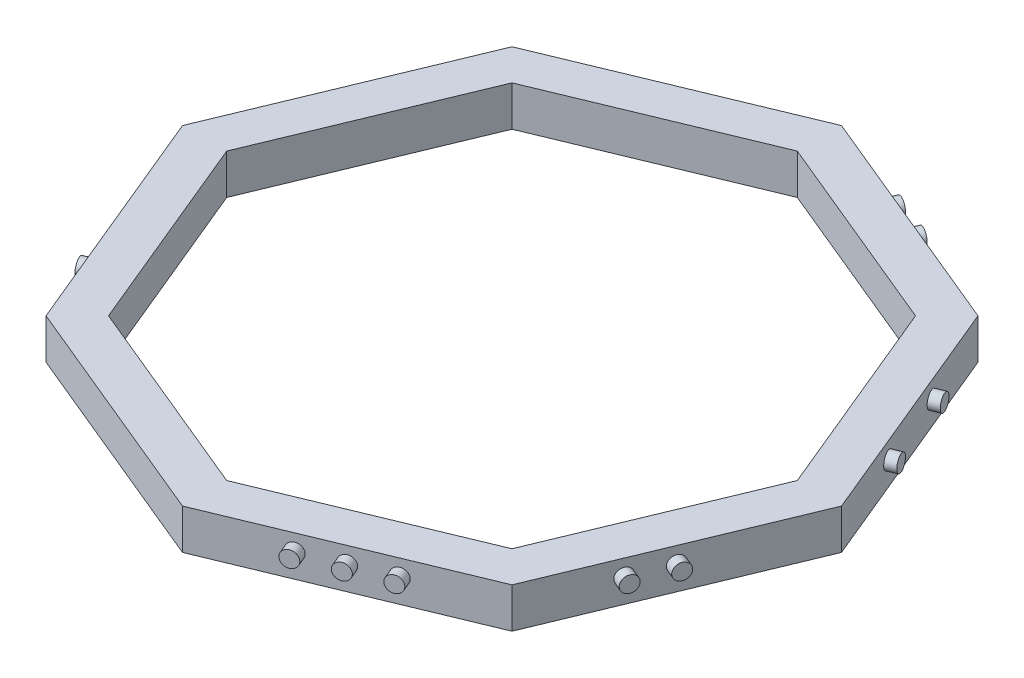
SolidWorks part; units mm, degrees
ref_plane "Front Plane" through (0, 0, 0) normal (0, 0, 1) x (1, 0, 0)
ref_plane "Top Plane" through (0, 0, 0) normal (0, 1, 0) x (1, 0, 0)
ref_plane "Right Plane" through (0, 0, 0) normal (1, 0, 0) x (0, 0, -1)
sketch "Sketch3" plane through (0, 0, 0) normal (0, 1, 0) x (1, 0, 0)
  line L1 (41, 0) -> (28.9914, 28.9914)
  line L2 (28.9914, 28.9914) -> (0, 41)
  line L3 (0, 41) -> (-28.9914, 28.9914)
  line L4 (-28.9914, 28.9914) -> (-41, 0)
  line L5 (-41, 0) -> (-28.9914, -28.9914)
  line L6 (-28.9914, -28.9914) -> (0, -41)
  line L7 (0, -41) -> (28.9914, -28.9914)
  line L8 (28.9914, -28.9914) -> (41, 0)
  circle A0 centre (0, 0) radius 37.8791 construction
  dimension "D1" = 41
extrude "Boss-Extrude1" add sketch "Sketch3" along normal blind 5
sketch "Sketch5" plane through (0, 5, 0) normal (0, 1, 0) x (1, 0, 0)
  line L1 (35.5, 0) -> (25.1023, 25.1023)
  line L2 (25.1023, 25.1023) -> (0, 35.5)
  line L3 (0, 35.5) -> (-25.1023, 25.1023)
  line L4 (-25.1023, 25.1023) -> (-35.5, 0)
  line L5 (-35.5, 0) -> (-25.1023, -25.1023)
  line L6 (-25.1023, -25.1023) -> (0, -35.5)
  line L7 (0, -35.5) -> (25.1023, -25.1023)
  line L8 (25.1023, -25.1023) -> (35.5, 0)
  circle A0 centre (0, 0) radius 32.7977 construction
  dimension "D1" = 35.5
extrude "Cut-Extrude1" cut sketch "Sketch5" against normal blind 5
sketch "Sketch6" plane through (14.4957, 0, 34.9957) normal (0.3827, 0, 0.9239) x (0.9239, 0, -0.3827)
  circle A0 centre (0, 3) radius 1
  circle A1 centre (-5, 3) radius 1
  circle A2 centre (5, 3) radius 1
sketch "Sketch7" plane through (-34.9957, 0, 14.4957) normal (-0.9239, 0, 0.3827) x (0.3827, 0, 0.9239)
  circle A0 centre (5, 3) radius 1
sketch "Sketch8" plane through (-34.9957, 0, -14.4957) normal (-0.9239, 0, -0.3827) x (-0.3827, 0, 0.9239)
  circle A0 centre (0, 3) radius 1
sketch "Sketch9" plane through (-14.4957, 0, -34.9957) normal (-0.3827, 0, -0.9239) x (-0.9239, 0, 0.3827)
  circle A0 centre (-5, 3) radius 1
sketch "Sketch10" plane through (14.4957, 0, -34.9957) normal (0.3827, 0, -0.9239) x (-0.9239, 0, -0.3827)
  circle A0 centre (0, 3) radius 1
  circle A1 centre (5, 3) radius 1
sketch "Sketch11" plane through (34.9957, 0, -14.4957) normal (0.9239, 0, -0.3827) x (-0.3827, 0, -0.9239)
  circle A0 centre (5, 3) radius 1
  circle A1 centre (-5, 3) radius 1
sketch "Sketch12" plane through (34.9957, 0, 14.4957) normal (0.9239, 0, 0.3827) x (0.3827, 0, -0.9239)
  circle A0 centre (0, 3) radius 1
  circle A1 centre (-5, 3) radius 1
extrude "Boss-Extrude5" add sketch "Sketch6" along normal blind 1.25 contours A2 | A1 | A0
extrude "Boss-Extrude6" add sketch "Sketch7" along normal blind 1.25 contours A0
extrude "Boss-Extrude7" add sketch "Sketch8" along normal blind 1.25 contours A0
extrude "Boss-Extrude8" add sketch "Sketch9" along normal blind 1.25 contours A0
extrude "Boss-Extrude12" add sketch "Sketch10" along normal blind 1.25 contours A0 | A1
extrude "Boss-Extrude13" add sketch "Sketch11" along normal blind 1.25 contours A1 | A0
extrude "Boss-Extrude14" add sketch "Sketch12" along normal blind 1.25 contours A1 | A0
